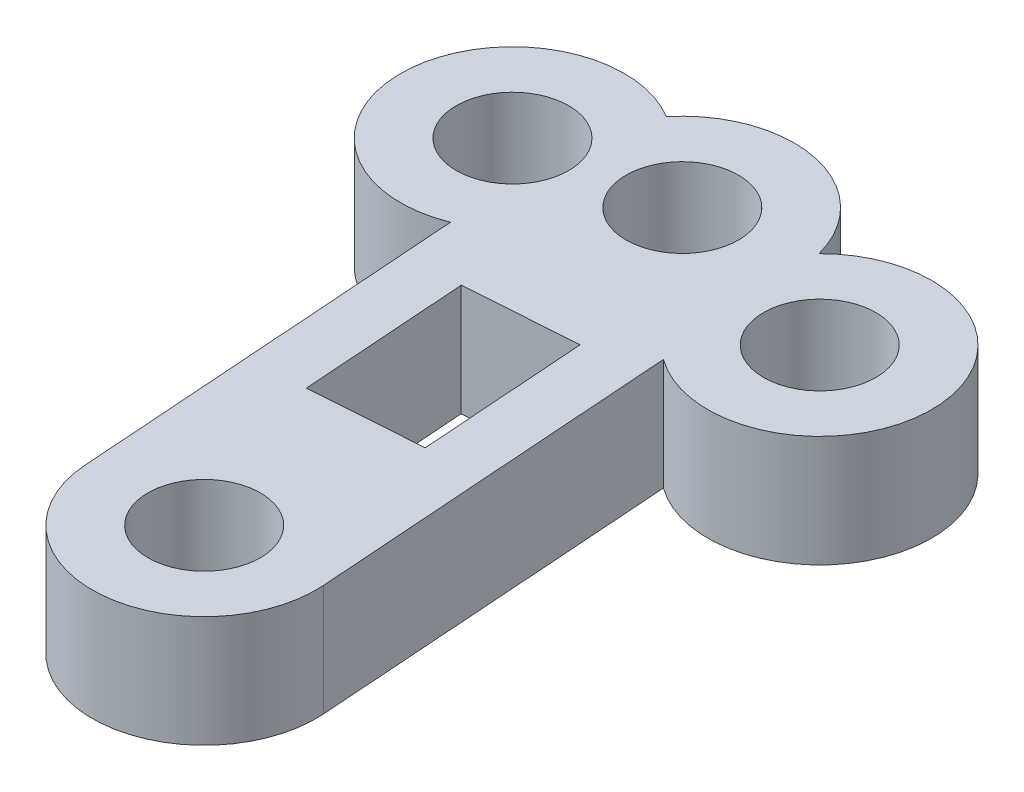
SolidWorks part; units mm, degrees
ref_plane "Front Plane" through (0, 0, 0) normal (0, 0, 1) x (1, 0, 0)
ref_plane "Top Plane" through (0, 0, 0) normal (0, 1, 0) x (1, 0, 0)
ref_plane "Right Plane" through (0, 0, 0) normal (1, 0, 0) x (0, 0, -1)
sketch "Sketch1" plane through (0, 0, 0) normal (0, 1, 0) x (1, 0, 0)
  line L0 (-9.9543, 33.2737) -> (-6.7117, -12.8977)
  line L1 (10.0963, 34.6819) -> (13.3389, -11.4895)
  circle A0 centre (-12.9537, 31.7552) radius 5.05
  circle A1 centre (0.071, 33.9778) radius 5.05
  circle A2 centre (3.3136, -12.1936) radius 5.05
  circle A3 centre (16.9279, 29.4608) radius 5.05
  circle A4 centre (-12.9537, 31.7552) radius 10.05
  circle A5 centre (0.071, 33.9778) radius 10.05
  circle A6 centre (3.3136, -12.1936) radius 10.05
  circle A7 centre (16.9279, 29.4608) radius 10.05
  point P0 (-12.9537, 31.7552)
  point P1 (0.071, 33.9778)
  point P2 (16.9279, 29.4608)
  point P3 (3.3136, -12.1936)
  point P15 (0, 0)
  point P26 (0, 0)
  dimension "D9" = 10.1
  dimension "D1" = 33.9778
  dimension "D2" = 31.7552
  dimension "D3" = 29.4608
  dimension "D4" = 12.1936
  dimension "D5" = 3.3136
  dimension "D6" = 16.9279
  dimension "D7" = 0.071
  dimension "D8" = 12.9537
  dimension "D10" = 5
extrude "Boss-Extrude1" add sketch "Sketch1" along normal blind 10 contours A7 A5 A4 L0 A6 L1 | A6 A2 | L1 A7 A5 A3 | A7 A5 A4 A1 | A5 A7 L1 | A5 A7 | A4 A5 A0 A1 | A5 A0 L0 A4 | A5 A4 L0 A0
sketch "Sketch2" plane through (0, 10, 0) normal (0, 1, 0) x (1, 0, 0)
  line L0 (-3.8208, 18.0234) -> (6.1546, 18.724)
  line L1 (-3.8208, 18.0234) -> (-2.77, 3.0602)
  line L2 (6.1546, 18.724) -> (7.2054, 3.7608)
  line L3 (-2.77, 3.0602) -> (7.2054, 3.7608)
  line L4 (-3.8208, 18.0234) -> (7.2054, 3.7608) construction
  line L5 (6.1546, 18.724) -> (-2.77, 3.0602) construction
  line L6 (11.0347, 21.32) -> (13.3389, -11.4895) construction
  line L9 (0.071, 33.9778) -> (3.3136, -12.1936) construction
  circle A0 centre (0.071, 33.9778) radius 5.05 construction
  circle A1 centre (3.3136, -12.1936) radius 5.05 construction
  point P0 (1.6923, 10.8921)
  point P1 (1.6923, 10.8921)
  point P8 (0, 0)
  dimension "D1" = 10
  dimension "D2" = 15
extrude "Cut-Extrude1" cut sketch "Sketch2" against normal blind 10
